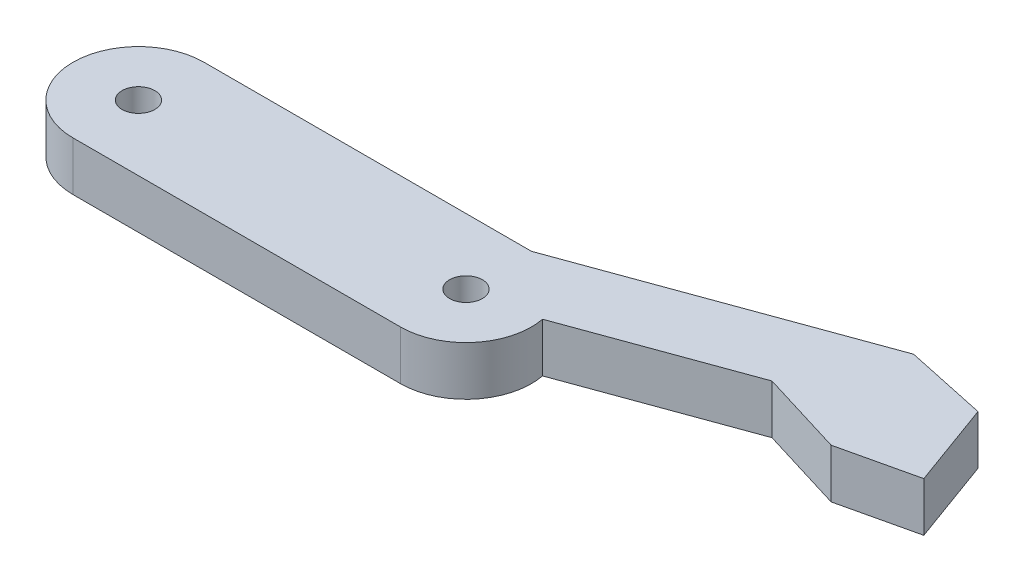
SolidWorks part; units mm, degrees
material "Oak"
ref_plane "Front" through (0, 0, 0) normal (0, 0, 1) x (1, 0, 0)
ref_plane "Top" through (0, 0, 0) normal (0, 1, 0) x (1, 0, 0)
ref_plane "Right" through (0, 0, 0) normal (1, 0, 0) x (0, 0, -1)
sketch "Sketch1" plane through (0, 0, 0) normal (0, 1, 0) x (1, 0, 0)
  line L0 (0, 86.6597) -> (0, -74.0832) construction
  line L1 (0, 0) -> (-100, 0) construction
  line L2 (0, -20) -> (-100, -20)
  line L3 (0, 20) -> (-100, 20)
  line L4 (0, 20) -> (85.5368, 51.1328)
  line L5 (85.5368, 51.1328) -> (110.5368, 45.7909)
  line L6 (110.5368, 45.7909) -> (120, 19.7909)
  line L7 (120, 19.7909) -> (97, 14.481)
  line L8 (97, 14.481) -> (71, 22.43)
  line L9 (71, 22.43) -> (19.6474, 3.7391)
  arc A0 (0, -20) -> (0, 20) centre (0, 0) ccw
  arc A1 (-100, 20) -> (-100, -20) centre (-100, 0) ccw
  point P5 (-50, 0)
  dimension "D2" = 20
  dimension "D1" = 100
  dimension "D3" = 70
  dimension "D4" = 22
  dimension "D5" = 120
  dimension "D6" = 25
  dimension "D7" = 26
  dimension "D8" = 23
  dimension "D9" = 26
  dimension "D10" = 77
  dimension "D11" = 73
extrude "Boss-Extrude1" add sketch "Sketch1" along normal blind 15 contours L3 A1 L2 A0 | A0 L9 L8 L7 L6 L5 L4
hole_wizard "Ø1.0mm Dowel Hole1" positions "Sketch3" profile "Sketch2" hole size "Ø1.0" standard "ANSI Metric" end condition through all
sketch "Sketch3" plane through (0, 15, 0) normal (0, 1, 0) x (1, 0, 0)
  arc A0 (-100, 20) -> (-100, -20) centre (-100, 0) ccw construction
  point P0 (-100, 0)
  point P2 (0, 0)
  dimension "D1" = 0
sketch "Sketch2" plane through (-100, 15, 0) normal (1, 0, 0) x (0, 0, 1)
  line L0 (0, 0) -> (0, 15)
  line L1 (0, 15) -> (5, 15)
  line L2 (5, 15) -> (5, 0)
  line L5 (5, 0) -> (0, 0)
  line L11 (0, -6.35) -> (0, 107.95) construction
  dimension "Thru Hole Dia." = 10
  dimension "Thru Hole Depth" = 15
scale "Escala1" scale about centroid uniform scaling yes scale factor 0.2
